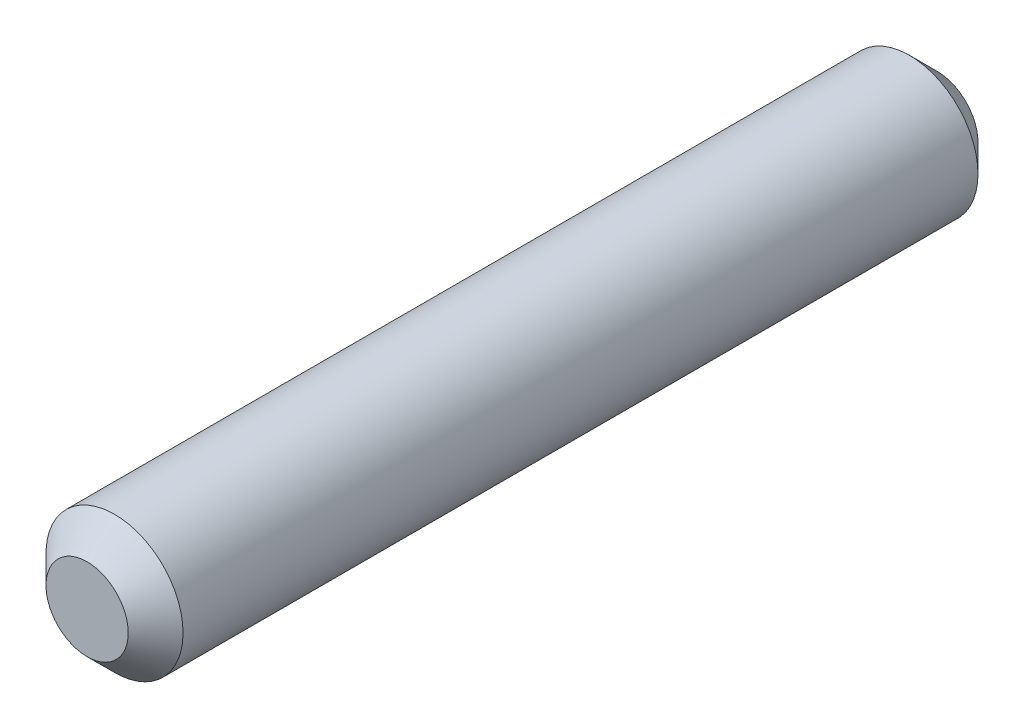
SolidWorks part; units mm, degrees
material "45"
ref_plane "前视基准面" through (0, 0, 0) normal (0, 0, 1) x (1, 0, 0)
ref_plane "上视基准面" through (0, 0, 0) normal (0, 1, 0) x (1, 0, 0)
ref_plane "右视基准面" through (0, 0, 0) normal (1, 0, 0) x (0, 0, -1)
sketch "草图1" plane through (0, 0, 0) normal (0, 0, 1) x (1, 0, 0)
  circle A0 centre (0, 0) radius 5
  dimension "D1" = 10
extrude "凸台-拉伸1" add sketch "草图1" along normal mid plane 62 contours A0
chamfer "倒角1" distance 2 angle 45 2 edges at (5, 0, -31) (5, 0, 31)
